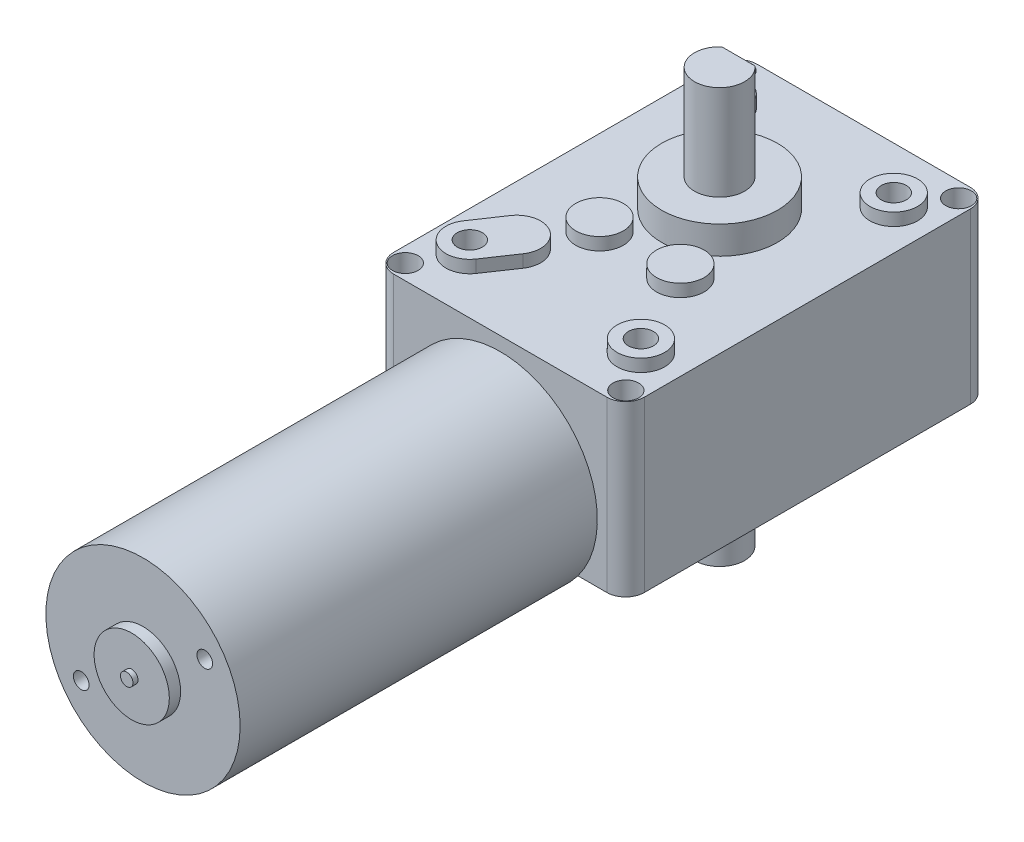
SolidWorks part; units mm, degrees
ref_plane "Front Plane" through (0, 0, 0) normal (0, 0, 1) x (1, 0, 0)
ref_plane "Top Plane" through (0, 0, 0) normal (0, 1, 0) x (1, 0, 0)
ref_plane "Right Plane" through (0, 0, 0) normal (1, 0, 0) x (0, 0, -1)
sketch "Sketch1" plane through (0, 0, 0) normal (0, 1, 0) x (1, 0, 0)
  line L1 (17.005, -29) -> (-17.005, -29)
  line L2 (20.005, -26) -> (20.005, 26)
  line L3 (17.005, 29) -> (-17.005, 29)
  line L4 (-20.005, -26) -> (-20.005, 26)
  line L5 (20.005, -29) -> (-20.005, 29) construction
  line L6 (20.005, 29) -> (-20.005, -29) construction
  arc A0 (-17.005, -29) -> (-20.005, -26) centre (-17.005, -26) cw
  arc A1 (17.005, -29) -> (20.005, -26) centre (17.005, -26) ccw
  arc A2 (20.005, 26) -> (17.005, 29) centre (17.005, 26) ccw
  arc A3 (-17.005, 29) -> (-20.005, 26) centre (-17.005, 26) ccw
  point P0 (0, 0)
  dimension "D1" = 40.01
  dimension "D2" = 58
  dimension "D3" = 3
extrude "Boss-Extrude2" add sketch "Sketch1" along normal blind 27
ref_plane "Plane1" through (0, 13.5, 0) normal (0, 1, 0) x (1, 0, 0)
sketch "Sketch5" plane through (0, 27, 0) normal (0, 1, 0) x (1, 0, 0)
  line L0 (-13.65, -20.2) -> (-10.6266, -15.7258) construction
  line L1 (-16.7985, -18.0724) -> (-13.7751, -13.5982)
  line L2 (-10.5015, -22.3276) -> (-7.478, -17.8534)
  line L3 (-17.005, -29) -> (17.005, -29) construction
  line L4 (0, -29) -> (0, 29) construction
  line L5 (17.005, 29) -> (-17.005, 29) construction
  circle A0 centre (-13.65, 20.15) radius 3.8
  circle A1 centre (13.65, 20.15) radius 3.8
  circle A2 centre (13.65, -20.2) radius 3.8
  arc A3 (-16.7985, -18.0724) -> (-10.5015, -22.3276) centre (-13.65, -20.2) ccw
  arc A4 (-7.478, -17.8534) -> (-13.7751, -13.5982) centre (-10.6266, -15.7258) ccw
  circle A5 centre (-6.45, -6.7) radius 3.8
  circle A6 centre (6.45, -6.7) radius 3.8
  point P8 (-12.1383, -17.9629)
  dimension "D2" = 5.4
  dimension "D5" = 12.9
  dimension "D7" = 22.3
  dimension "D6" = 7.6
  dimension "D8" = 7.6
  dimension "D1" = 7.6
  dimension "D3" = 40.35
  dimension "D4" = 8.8
  dimension "D9" = 27.3
extrude "Boss-Extrude3" add sketch "Sketch5" along normal blind 2
sketch "Sketch6" plane through (0, 29, 0) normal (0, 1, 0) x (1, 0, 0)
  circle A0 centre (13.65, -20.2) radius 2
  circle A1 centre (13.65, 20.15) radius 2
  circle A2 centre (-13.65, 20.15) radius 2
  circle A3 centre (-13.65, -20.2) radius 2
  arc A4 (-16.7985, -18.0724) -> (-10.5015, -22.3276) centre (-13.65, -20.2) ccw construction
  dimension "D1" = 4
extrude "Cut-Extrude3" cut sketch "Sketch6" against normal blind 4
sketch "Sketch7" plane through (0, 27, 0) normal (0, 1, 0) x (1, 0, 0)
  line L0 (-17.005, -29) -> (17.005, -29) construction
  circle A0 centre (0, 6) radius 9.25
  dimension "D1" = 18.5
  dimension "D2" = 35
extrude "Boss-Extrude4" add sketch "Sketch7" along normal blind 4.45
sketch "Sketch8" plane through (0, 31.45, 0) normal (0, 1, 0) x (1, 0, 0)
  circle A0 centre (0, 6) radius 4
  dimension "D1" = 8
extrude "Boss-Extrude5" add sketch "Sketch8" along normal blind 15.14
sketch "Sketch9" plane through (0, 46.59, 0) normal (0, 1, 0) x (1, 0, 0)
  line L0 (-2.6458, 9) -> (2.6458, 9)
  circle A0 centre (0, 6) radius 4 construction
  arc A1 (2.6458, 9) -> (-2.6458, 9) centre (0, 6) ccw
  dimension "D1" = 3
extrude "Cut-Extrude4" cut sketch "Sketch9" against normal blind 13
mirror "Mirror1" about plane through (0, 13.5, 0) normal (0, 1, 0) of "Cut-Extrude4", "Boss-Extrude5", "Boss-Extrude4", "Cut-Extrude3", "Boss-Extrude3"
sketch "Sketch11" plane through (0, 0, 29) normal (0, 0, 1) x (1, 0, 0)
  line L4 (-17.005, 0) -> (17.005, 0) construction
  circle A0 centre (0, 9.3) radius 15.5
  dimension "D1" = 31
  dimension "D2" = 9.3
extrude "Boss-Extrude6" add sketch "Sketch11" along normal blind 57
sketch "Sketch12" plane through (0, 0, 86) normal (0, 0, 1) x (1, 0, 0)
  circle A0 centre (0, 9.3) radius 6
  dimension "D1" = 12
extrude "Boss-Extrude7" add sketch "Sketch12" along normal blind 1.8
sketch "Sketch13" plane through (0, 0, 87.8) normal (0, 0, 1) x (1, 0, 0)
  circle A0 centre (0, 9.3) radius 1
  dimension "D1" = 2
extrude "Boss-Extrude8" add sketch "Sketch13" along normal blind 0.8
sketch "Sketch14" plane through (0, 0, 86) normal (0, 0, 1) x (1, 0, 0)
  line L0 (0, 9.3) -> (9.8544, 15.6995) construction
  line L1 (0, 9.3) -> (0, 24.8) construction
  circle A0 centre (0, 9.3) radius 11.75 construction
  circle A1 centre (9.8544, 15.6995) radius 1.25
  circle A3 centre (-9.8544, 2.9005) radius 1.25
  circle A4 centre (0, 9.3) radius 15.5 construction
  point P11 (0, 9.3)
  dimension "D1" = 23.5
  dimension "D2" = 57
  dimension "D3" = 2
  dimension "D4" = 2.5
extrude "Cut-Extrude6" cut sketch "Sketch14" against normal blind 4
sketch "Sketch10" plane through (0, 27, 0) normal (0, 1, 0) x (1, 0, 0)
  line L0 (0, 29) -> (0, -29) construction
  line L1 (17.005, 29) -> (-17.005, 29) construction
  line L2 (-17.005, -29) -> (17.005, -29) construction
  line L3 (-20.005, 0) -> (20.005, 0) construction
  line L4 (-20.005, 26) -> (-20.005, -26) construction
  line L5 (20.005, -26) -> (20.005, 26) construction
  circle A0 centre (-17.6, 26.55) radius 2.05
  circle A1 centre (17.6, 26.55) radius 2.05
  circle A2 centre (17.6, -26.55) radius 2.05
  circle A3 centre (-17.6, -26.55) radius 2.05
  dimension "D3" = 4.1
  dimension "D1" = 35.2
  dimension "D2" = 2.45
extrude "Cut-Extrude5" cut sketch "Sketch10" against normal blind 4
